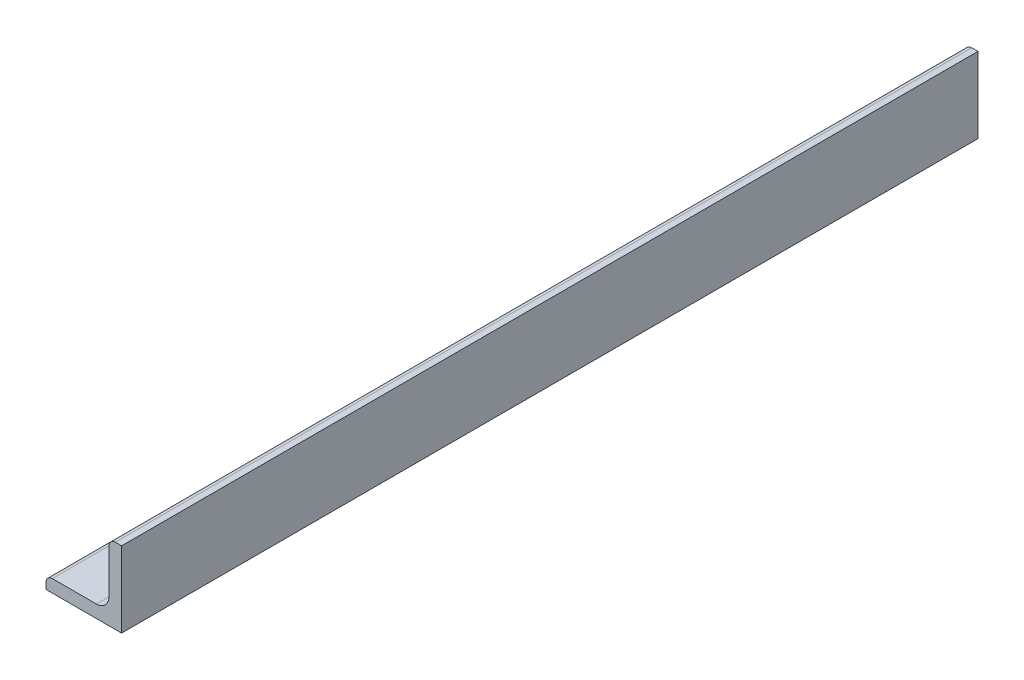
SolidWorks part; units mm, degrees
material "6061 Alloy"
ref_plane "Front Plane" through (0, 0, 0) normal (0, 0, 1) x (1, 0, 0)
ref_plane "Top Plane" through (0, 0, 0) normal (0, 1, 0) x (1, 0, 0)
ref_plane "Right Plane" through (0, 0, 0) normal (1, 0, 0) x (0, 0, -1)
sketch "Sketch2" plane through (0, 0, 0) normal (0, 0, 1) x (1, 0, 0)
  line L0 (-9.525, 0) -> (9.525, 0)
  line L1 (9.525, 0) -> (9.525, 19.05)
  line L2 (9.525, 19.05) -> (6.35, 19.05) construction
  line L3 (6.35, 17.4625) -> (6.35, 6.35)
  line L4 (3.175, 3.175) -> (-7.9375, 3.175)
  line L5 (-9.525, 0) -> (-9.525, 3.175) construction
  line L6 (7.9375, 19.05) -> (9.525, 19.05)
  line L7 (-9.525, 1.5875) -> (-9.525, 0)
  arc A0 (6.35, 17.4625) -> (7.9375, 19.05) centre (7.9375, 17.4625) cw
  arc A1 (-9.525, 1.5875) -> (-7.9375, 3.175) centre (-7.9375, 1.5875) cw
  arc A2 (6.35, 6.35) -> (3.175, 3.175) centre (3.175, 6.35) cw
  dimension "Inside Radius" = 3.175
  dimension "Vert" = 19.05
  dimension "Horz" = 19.05
  dimension "Thickness" = 3.175
extrude "Boss-Extrude1" add sketch "Sketch2" along normal mid plane 215.9
sketch "Break Locations" plane through (0, 0, 0) normal (1, 0, 0) x (0, 0, -1)
  line L1 (-107.95, 0) -> (-107.95, 19.05) construction
  line L2 (107.95, 0) -> (107.95, 19.05) construction
  point P0 (-91.7575, 0)
  point P1 (91.7575, 0)
  dimension "D1" = 16.1925
  dimension "D2" = 16.1925
ref_plane "Contact Plane 1" through (0, 3.175, 0) normal (0, 1, 0) x (1, 0, 0)
ref_plane "Contact Plane 2" through (6.35, 0, 0) normal (-1, 0, 0) x (0, 0, 1)
sketch "Sketch3" plane through (0, 3.175, 0) normal (0, 1, 0) x (1, 0, 0)
  point P0 (-0.2937, 95.25)
  point P1 (-0.2937, -95.25)
hole_wizard "#6-32 Tapped Hole1" positions "Sketch4" profile "Sketch6" tap size "#6-32" standard "ANSI Inch" end condition through all
sketch "Sketch4" plane through (0, 3.175, 0) normal (0, 1, 0) x (1, 0, 0)
  point P0 (-0.2937, -95.25)
  point P3 (-0.2937, 95.25)
sketch "Sketch6" plane through (-0.2937, 3.175, 95.25) normal (1, 0, 0) x (0, 0, 1)
  line L0 (0, 0) -> (0, 3.175)
  line L1 (0, 3.175) -> (1.3525, 3.175)
  line L2 (1.3525, 3.175) -> (1.3525, 0)
  line L5 (1.3525, 0) -> (0, 0)
  line L11 (0, -6.35) -> (0, 107.95) construction
  dimension "Thru Tap Drill Dia." = 2.7051
  dimension "Thru Tap Drill Depth" = 3.175
cosmetic thread "Hole Thread4" parameters "D1"=7.112, "D2"=3.7051
cosmetic thread "Hole Thread5" parameters "D1"=7.112, "D2"=3.7051
equation "\"D1@Break Locations\"=.85*\"Vert@Sketch2\""
equation "\"D2@Break Locations\"=\"D1@Break Locations\""
